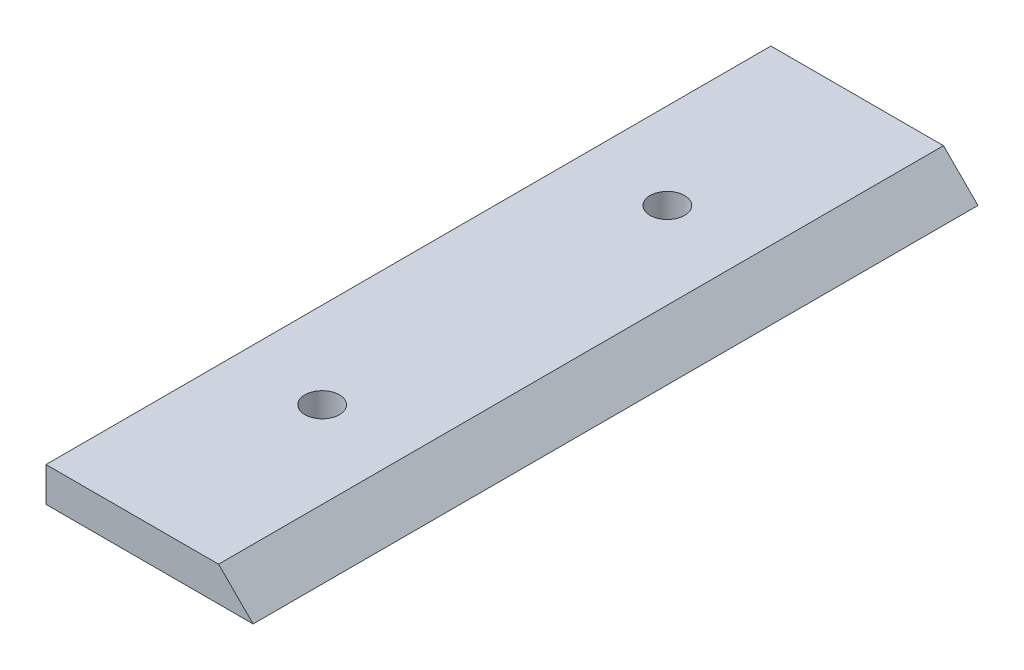
SolidWorks part; units mm, degrees
ref_plane "Front Plane" through (0, 0, 0) normal (0, 0, 1) x (1, 0, 0)
ref_plane "Top Plane" through (0, 0, 0) normal (0, 1, 0) x (1, 0, 0)
ref_plane "Right Plane" through (0, 0, 0) normal (1, 0, 0) x (0, 0, -1)
sketch "Sketch1" plane through (0, 0, 0) normal (0, 0, 1) x (1, 0, 0)
  line L0 (-76.5089, 0) -> (76.5089, 0) construction
  line L1 (0, -66.4107) -> (0, 66.4107) construction
  line L2 (25, 5) -> (35, -5)
  line L3 (-25, -5) -> (25, -5)
  line L4 (-25, -5) -> (-25, 5)
  line L5 (-25, 5) -> (25, 5)
  line L6 (25, -5) -> (25, 5) construction
  line L7 (-25, -5) -> (25, 5) construction
  line L8 (-25, 5) -> (25, -5) construction
  line L9 (35, -5) -> (25, -5)
  point P0 (0, 0)
  point P4 (0, 0)
  point P8 (0, 0)
  dimension "D1" = 10
  dimension "D2" = 50
  dimension "D3" = 10
extrude "Boss-Extrude1" add sketch "Sketch1" along normal mid plane 210
sketch "Sketch2" plane through (0, 0, 0) normal (0, 1, 0) x (1, 0, 0)
  line L0 (-134.9801, 0) -> (134.9801, 0) construction
  line L1 (0, -197.173) -> (0, 197.173) construction
  circle A0 centre (0, 50) radius 5
  circle A1 centre (0, -50) radius 5
  point P4 (0, 0)
  point P8 (0, 0)
  dimension "D1" = 10
  dimension "D2" = 50
extrude "Cut-Extrude1" cut sketch "Sketch2" along normal blind 50 and the other way blind 50
